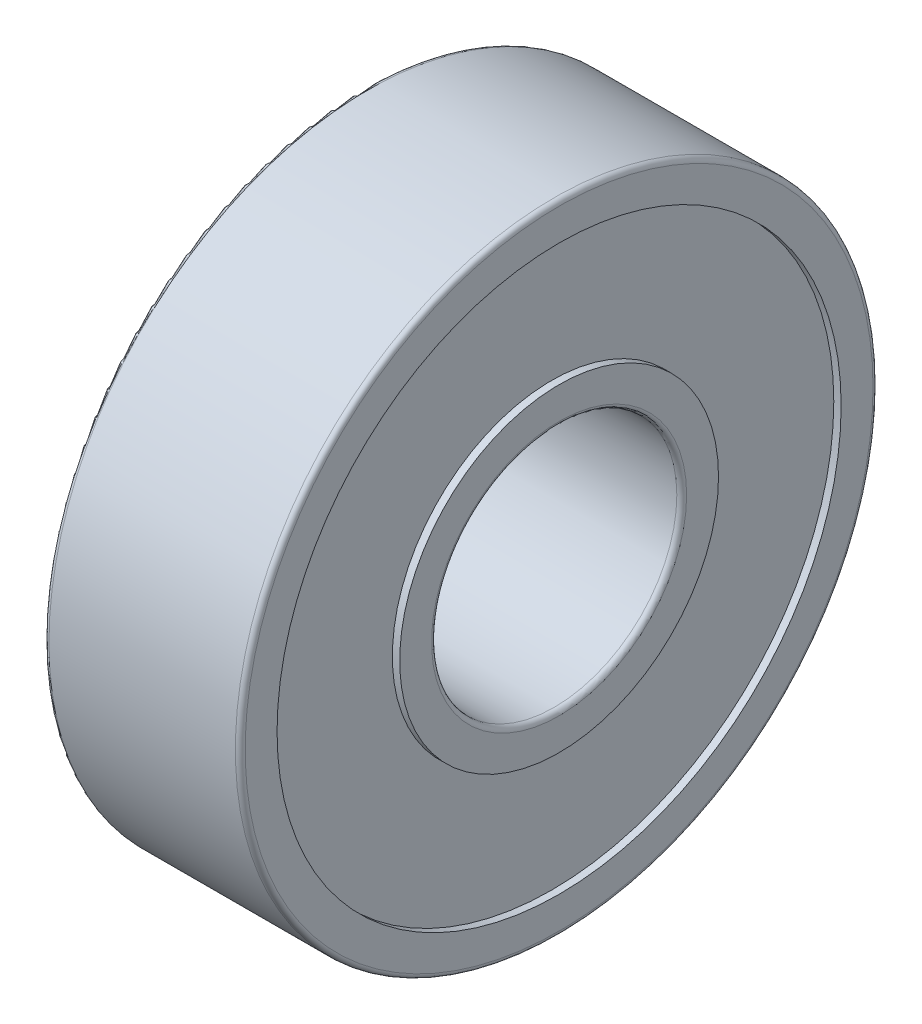
SolidWorks part; units mm, degrees
material "Plain Carbon Steel"
ref_plane "Front Plane" through (0, 0, 0) normal (0, 0, 1) x (1, 0, 0)
ref_plane "Top Plane" through (0, 0, 0) normal (0, 1, 0) x (1, 0, 0)
ref_plane "Right Plane" through (0, 0, 0) normal (1, 0, 0) x (0, 0, -1)
sketch "Sketch1" plane through (0, 0, 0) normal (0, 0, 1) x (1, 0, 0)
  line L0 (4, 5) -> (-4, 5)
  line L1 (-4, 5) -> (-4, 6.5)
  line L2 (-4, 6.5) -> (-3.7, 6.5)
  line L3 (-3.7, 6.5) -> (-3.7, 11.5)
  line L4 (-3.7, 11.5) -> (-4, 11.5)
  line L5 (-4, 11.5) -> (-4, 13)
  line L6 (-4, 13) -> (4, 13)
  line L7 (0, 13) -> (0, 5) construction
  line L8 (4, 11.5) -> (4, 13)
  line L9 (3.7, 11.5) -> (4, 11.5)
  line L10 (3.7, 6.5) -> (3.7, 11.5)
  line L11 (4, 6.5) -> (3.7, 6.5)
  line L12 (4, 5) -> (4, 6.5)
  line L13 (0, 0) -> (-4.3663, 0) construction
  dimension "D1" = 10
  dimension "D2" = 26
  dimension "D3" = 8
  dimension "D4" = 1.5
  dimension "D5" = 1.5
  dimension "D6" = 0.3
revolve "Revolve1" add sketch "Sketch1" angle 360 about L13
fillet "Fillet1" radius 0.2 4 edges at (-4, 0, -13) (4, 0, -13) (-4, 0, -5) (4, 0, -5)
